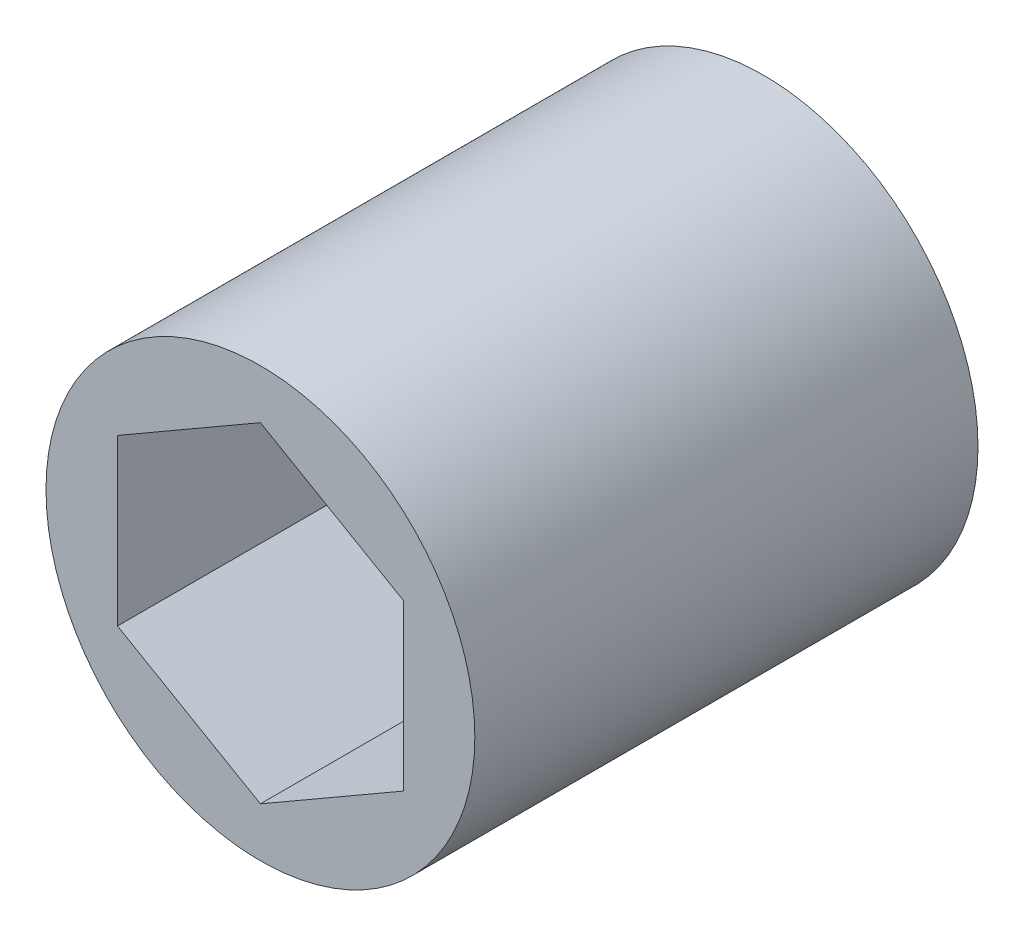
SolidWorks part; units mm, degrees
material "Nylon 101"
ref_plane "Front Plane" through (0, 0, 0) normal (0, 0, 1) x (1, 0, 0)
ref_plane "Top Plane" through (0, 0, 0) normal (0, 1, 0) x (1, 0, 0)
ref_plane "Right Plane" through (0, 0, 0) normal (1, 0, 0) x (0, 0, -1)
sketch "Sketch1" plane through (0, 0, 0) normal (0, 0, 1) x (1, 0, 0)
  line L1 (0, 7.3323) -> (-6.35, 3.6662)
  line L2 (-6.35, 3.6662) -> (-6.35, -3.6662)
  line L3 (-6.35, -3.6662) -> (0, -7.3323)
  line L4 (0, -7.3323) -> (6.35, -3.6662)
  line L5 (6.35, -3.6662) -> (6.35, 3.6662)
  line L6 (6.35, 3.6662) -> (0, 7.3323)
  circle A0 centre (0, 0) radius 9.525
  circle A1 centre (0, 0) radius 6.35 construction
  dimension "D1" = 19.05
  dimension "D2" = 12.7
extrude "Boss-Extrude1" add sketch "Sketch1" along normal blind 22.352
